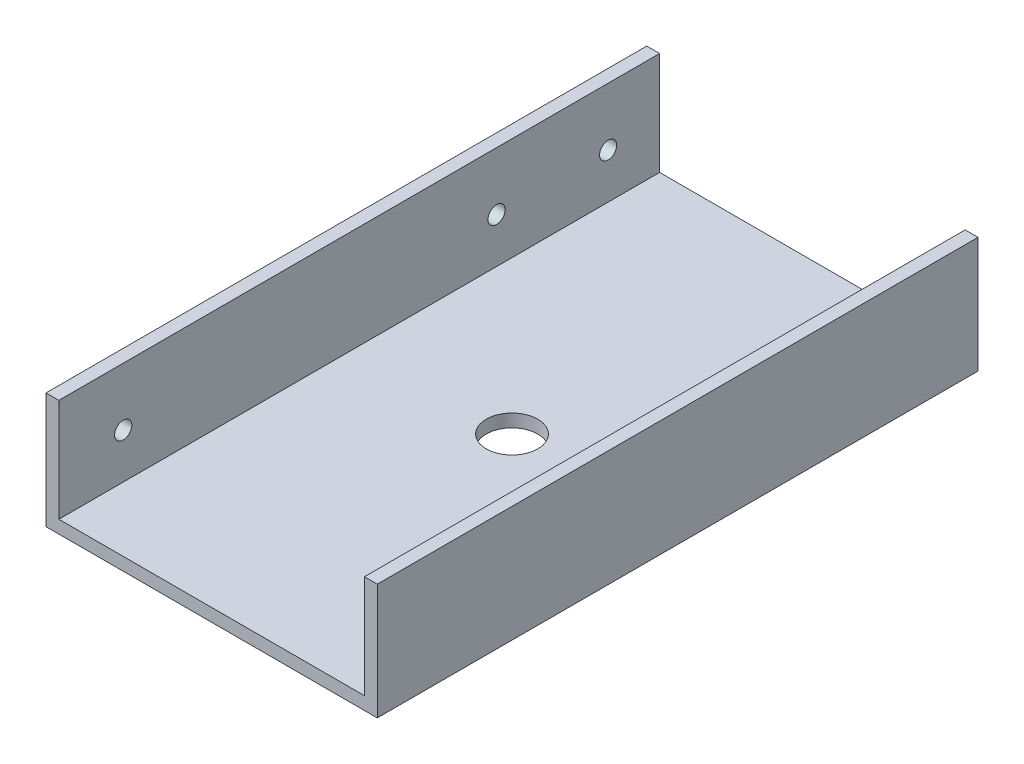
SolidWorks part; units mm, degrees
ref_plane "Ön Düzlem" through (0, 0, 0) normal (0, 0, 1) x (1, 0, 0)
ref_plane "Üst Düzlem" through (0, 0, 0) normal (0, 1, 0) x (1, 0, 0)
ref_plane "Sağ Düzlem" through (0, 0, 0) normal (1, 0, 0) x (0, 0, -1)
sketch "Sketch1" plane through (0, 0, 0) normal (0, 0, 1) x (1, 0, 0)
  line L0 (-19.3, 13.5) -> (-19.3, 0)
  line L1 (-19.3, 0) -> (19.3, 0)
  line L2 (19.3, 0) -> (19.3, 13.5)
  line L3 (-17.8, 13.5) -> (-17.8, 1.5)
  line L4 (-17.8, 1.5) -> (17.8, 1.5)
  line L5 (17.8, 1.5) -> (17.8, 13.5)
  line L6 (17.8, 13.5) -> (19.3, 13.5)
  line L7 (-19.3, 13.5) -> (-17.8, 13.5)
  dimension "D1" = 38.6
  dimension "D2" = 13.5
  dimension "D3" = 1.5
extrude "Boss-Extrude1" add sketch "Sketch1" along normal mid plane 70
sketch "Sketch2" plane through (0, 0, 0) normal (0, -1, 0) x (1, 0, 0)
  circle A0 centre (0, 0) radius 3
  dimension "D1" = 6
extrude "Cut-Extrude1" cut sketch "Sketch2" against normal through all
sketch "Sketch4" plane through (-19.3, 0, 0) normal (-1, 0, 0) x (0, 0, 1)
  line L0 (-29, 6.75) -> (-35, 6.75) construction
  line L1 (-35, 13.5) -> (-35, 0) construction
  line L2 (35, 13.5) -> (35, 0) construction
  circle A0 centre (-29, 6.75) radius 1
  circle A1 centre (-16, 6.75) radius 1
  circle A2 centre (27.5, 6.75) radius 1
  dimension "D1" = 2
  dimension "D2" = 6
  dimension "D3" = 19
  dimension "D4" = 7.5
extrude "Cut-Extrude3" cut sketch "Sketch4" against normal up to next
